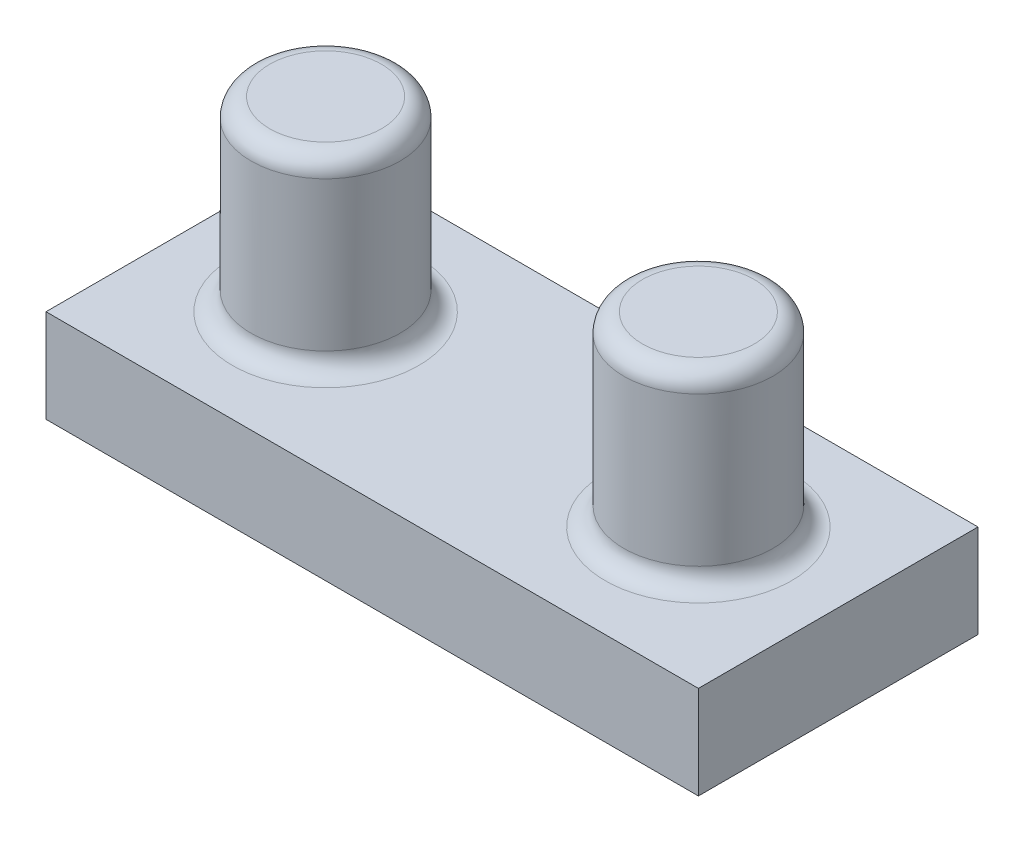
SolidWorks part; units mm, degrees
ref_plane "Front Plane" through (0, 0, 0) normal (0, 0, 1) x (1, 0, 0)
ref_plane "Top Plane" through (0, 0, 0) normal (0, 1, 0) x (1, 0, 0)
ref_plane "Right Plane" through (0, 0, 0) normal (1, 0, 0) x (0, 0, -1)
sketch "Sketch1" plane through (0, 0, 0) normal (0, 1, 0) x (1, 0, 0)
  line L0 (34.9998, 7.1697) -> (-26.696, 7.1697) construction
  circle A0 centre (9.0867, 7.1697) radius 4
  circle A1 centre (-10.9133, 7.1697) radius 4
  point P6 (0, 0)
  dimension "D1" = 20
  dimension "D2" = 8
  dimension "D3" = 8
extrude "Boss-Extrude1" add sketch "Sketch1" along normal blind 10
sketch "Sketch2" plane through (0, 0, 0) normal (0, -1, 0) x (-1, 0, 0)
  line L1 (18.4133, -0.3303) -> (-16.5867, -0.3303)
  line L2 (18.4133, -0.3303) -> (18.4133, 14.6697)
  line L3 (18.4133, 14.6697) -> (-16.5867, 14.6697)
  line L4 (-16.5867, -0.3303) -> (-16.5867, 14.6697)
  circle A0 centre (10.9133, 7.1697) radius 4 construction
  dimension "D1" = 35
  dimension "D2" = 7.5
  dimension "D3" = 15
  dimension "D4" = 7.5
extrude "Boss-Extrude2" add sketch "Sketch2" along normal blind 5
fillet "Fillet1" radius 1 4 edges at (-10.9133, 0, -11.1697) (9.0867, 0, -3.1697) (-10.9133, 10, -3.1697) (9.0867, 10, -3.1697)
sketch "Sketch3" plane through (0, 0, -14.6697) normal (0, 0, -1) x (-1, 0, 0)
  line L0 (15.3805, -4.4112) -> (-14.2204, -4.4112) construction
  text T0 "20 mm"
extrude "Cut-Extrude1" cut sketch "Sketch3" against normal blind 1
